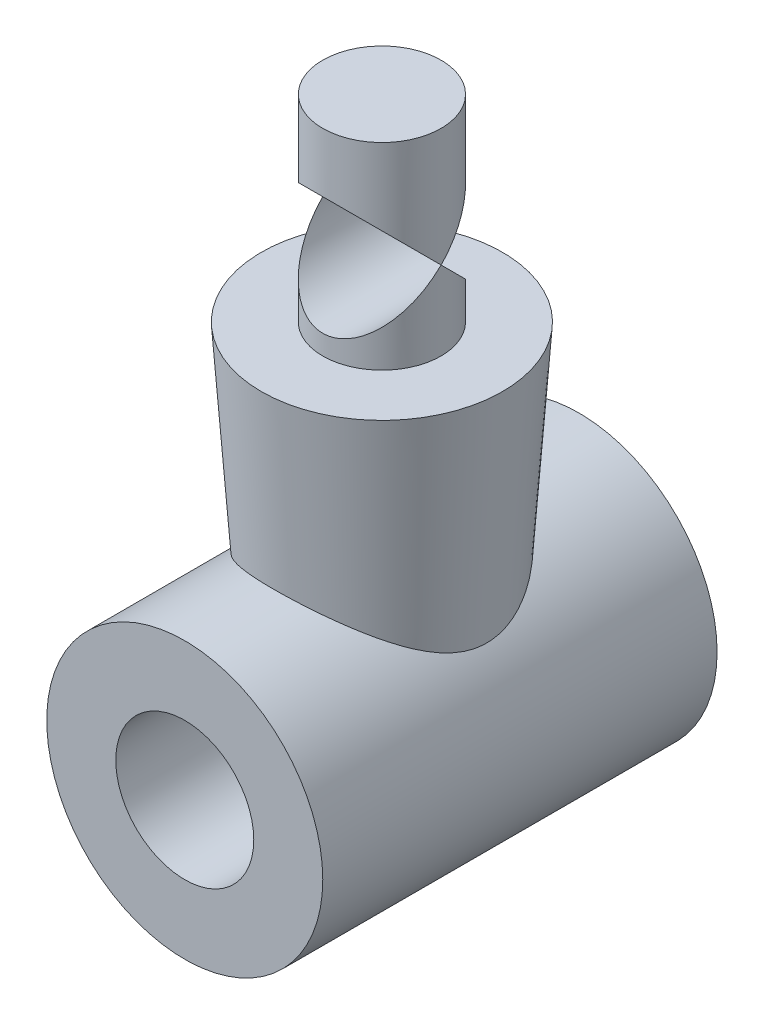
SolidWorks part; units mm, degrees
ref_plane "Front Plane" through (0, 0, 0) normal (0, 0, 1) x (1, 0, 0)
ref_plane "Top Plane" through (0, 0, 0) normal (0, 1, 0) x (1, 0, 0)
ref_plane "Right Plane" through (0, 0, 0) normal (1, 0, 0) x (0, 0, -1)
sketch "Sketch1" plane through (0, 0, 0) normal (0, 0, 1) x (1, 0, 0)
  circle A0 centre (0, 0) radius 35
  dimension "D1" = 70
extrude "Boss-Extrude1" add sketch "Sketch1" along normal mid plane 100
sketch "Sketch2" plane through (0, 0, 0) normal (0, 1, 0) x (1, 0, 0)
  circle A0 centre (0, 0) radius 25
  dimension "D1" = 50
extrude "Boss-Extrude2" add sketch "Sketch2" along normal blind 80 draft 4 draft outward yes
sketch "Sketch4" plane through (0, 0, 50) normal (0, 0, 1) x (1, 0, 0)
  circle A0 centre (0, 0) radius 17.5
  dimension "D1" = 35
sketch "Sketch7" plane through (0, 80, 0) normal (0, 1, 0) x (1, 0, 0)
  circle A0 centre (0, 0) radius 15
  dimension "D1" = 30
sketch "Sketch8" plane through (0, 0, -50) normal (0, 0, -1) x (-1, 0, 0)
  circle A0 centre (0, 0) radius 15
  dimension "D1" = 30
extrude "Cut-Extrude5" cut sketch "Sketch8" against normal through all
extrude "Boss-Extrude3" add sketch "Sketch7" along normal blind 50 contours A0
extrude "Cut-Extrude2" cut sketch "Sketch4" against normal through all
sketch "Sketch6" plane through (0, 0, 50) normal (0, 0, 1) x (1, 0, 0)
  line L0 (0, 80) -> (0, 22.8125) construction
  circle A0 centre (0, 100) radius 15
  dimension "D1" = 30
  dimension "D2" = 100
extrude "Cut-Extrude3" cut sketch "Sketch6" against normal through all
